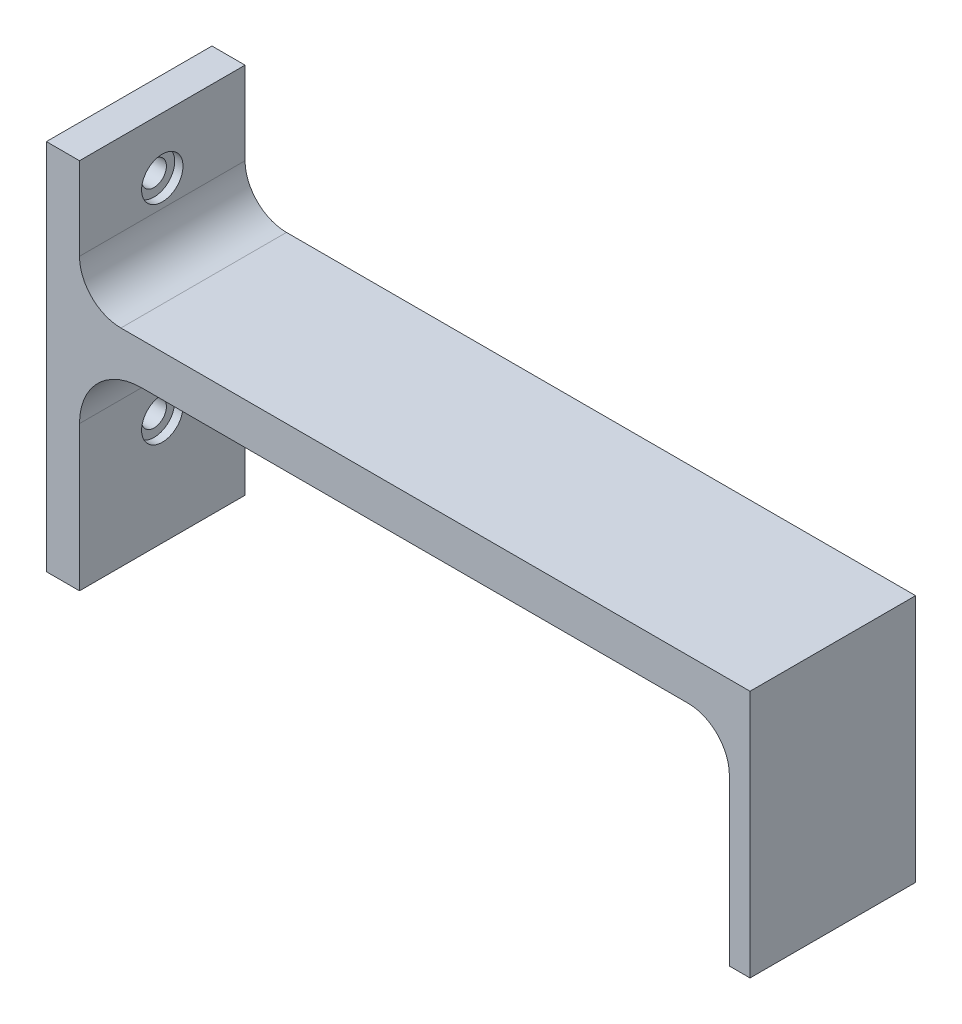
SolidWorks part; units mm, degrees
ref_plane "Front Plane" through (0, 0, 0) normal (0, 0, 1) x (1, 0, 0)
ref_plane "Top Plane" through (0, 0, 0) normal (0, 1, 0) x (1, 0, 0)
ref_plane "Right Plane" through (0, 0, 0) normal (1, 0, 0) x (0, 0, -1)
sketch "Esquisse2" plane through (0, 0, 0) normal (0, 1, 0) x (1, 0, 0)
  line L5 (-85, 20) -> (85, 20)
  line L6 (-85, 20) -> (-85, -20)
  line L7 (-85, -20) -> (85, -20)
  line L8 (85, 20) -> (85, -20)
  line L9 (-85, 20) -> (85, -20) construction
  line L10 (-85, -20) -> (85, 20) construction
  point P0 (0, 0)
  point P4 (0, 0)
  dimension "D1" = 40
extrude "Boss.-Extru.1" add sketch "Esquisse2" along normal blind 10
sketch "Esquisse3" plane through (0, 0, 0) normal (0, -1, 0) x (1, 0, 0)
  line L0 (85, -20) -> (-85, -20) construction
  line L1 (-85, 20) -> (-77, 20)
  line L2 (-85, 20) -> (-85, -20)
  line L3 (-85, -20) -> (-77, -20)
  line L4 (-77, 20) -> (-77, -20)
  dimension "D1" = 8
extrude "Boss.-Extru.2" add sketch "Esquisse3" along normal blind 50
sketch "Esquisse4" plane through (0, 0, 0) normal (0, -1, 0) x (1, 0, 0)
  line L0 (85, -20) -> (-77, -20) construction
  line L1 (85, 20) -> (80, 20)
  line L2 (85, 20) -> (85, -20)
  line L3 (85, -20) -> (80, -20)
  line L4 (80, 20) -> (80, -20)
  dimension "D1" = 5
extrude "Boss.-Extru.3" add sketch "Esquisse4" along normal blind 50
fillet "Congé1" radius 15 1 edges at (-77, 0, 0)
fillet "Congé2" radius 10 1 edges at (80, 0, 0)
sketch "Esquisse7" plane through (0, 10, 0) normal (0, 1, 0) x (1, 0, 0)
  line L0 (85, 20) -> (-85, 20) construction
  line L1 (-85, -20) -> (-77, -20)
  line L2 (-85, -20) -> (-85, 20)
  line L3 (-85, 20) -> (-77, 20)
  line L4 (-77, -20) -> (-77, 20)
  dimension "D1" = 8
extrude "Boss.-Extru.4" add sketch "Esquisse7" along normal blind 30
fillet "Congé3" radius 10 1 edges at (-77, 10, 0)
sketch "Esquisse8" plane through (-85, 0, 0) normal (-1, 0, 0) x (0, 0, 1)
  circle A0 centre (0, 26.3866) radius 3
  circle A1 centre (0, -23.9077) radius 3
extrude "Enlèv. mat.-Extru.3" cut sketch "Esquisse8" against normal up to next
sketch "Esquisse10" plane through (-77, 0, 0) normal (1, 0, 0) x (0, 0, -1)
  circle A0 centre (0, -23.9077) radius 5
extrude "Enlèv. mat.-Extru.4" cut sketch "Esquisse10" against normal blind 2
sketch "Esquisse11" plane through (-77, 0, 0) normal (1, 0, 0) x (0, 0, -1)
  circle A0 centre (0, 26.3866) radius 5
extrude "Enlèv. mat.-Extru.5" cut sketch "Esquisse11" against normal blind 2
sketch "Esquisse12" plane through (-85, 0, 0) normal (-1, 0, 0) x (0, 0, 1)
  line L1 (20, 40) -> (20, -50) construction
  line L2 (20, 23.3866) -> (-20, 23.3866) construction
  line L3 (-20, 40) -> (-20, -50) construction
  circle A0 centre (0, 26.3866) radius 3 construction
  point P0 (0, 23.3866)
